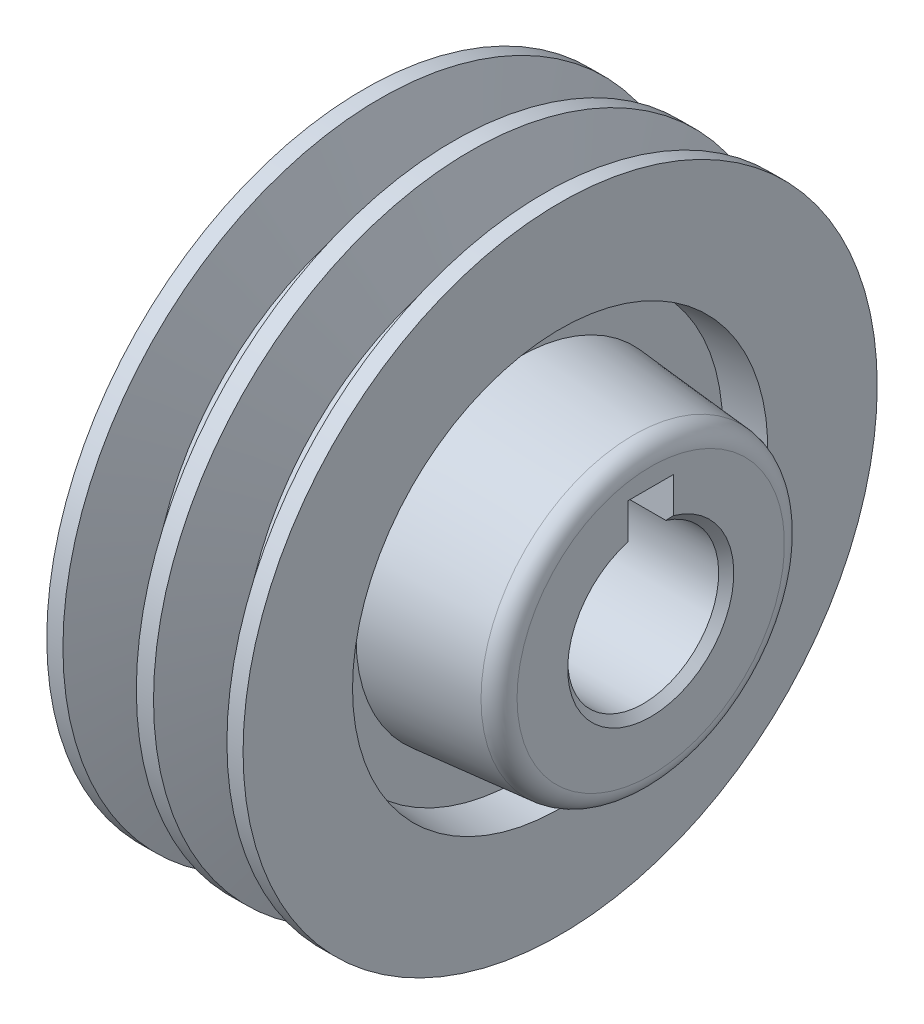
SolidWorks part; units mm, degrees
ref_plane "前视基准面" through (0, 0, 0) normal (0, 0, 1) x (1, 0, 0)
ref_plane "上视基准面" through (0, 0, 0) normal (0, 1, 0) x (1, 0, 0)
ref_plane "右视基准面" through (0, 0, 0) normal (1, 0, 0) x (0, 0, -1)
sketch "草图1" plane through (0, 0, 0) normal (0, 0, 1) x (1, 0, 0)
  line L0 (0, 0) -> (64.8368, 0) construction
  line L1 (-12, 10) -> (-12, 20)
  line L2 (0, 42) -> (26, 42)
  line L3 (26, 42) -> (26, 27.5)
  line L4 (-12, 20) -> (-41, 20) construction
  line L5 (5.5, 21.5311) -> (5.5, 27.0188)
  line L6 (38, 10) -> (-12, 10)
  line L7 (2.1385, 42) -> (4.8901, 33) construction
  line L8 (4.8901, 33) -> (9.1099, 33) construction
  line L9 (9.1099, 33) -> (11.8615, 42) construction
  line L10 (0, 40) -> (26, 40) construction
  line L11 (7, 33) -> (7, 10) construction
  line L12 (44, 27.5) -> (0, 27.5) construction
  line L13 (26, 27.5) -> (79, 27.5) construction
  line L14 (20.5, 27.0188) -> (20.5, 21.5311)
  line L15 (-6, 20) -> (38, 20) construction
  line L16 (13, 10) -> (13, 42) construction
  line L17 (38, 20) -> (38, 10)
  line L18 (0, 27.5) -> (0, 42)
  line L19 (5.5, 25.5) -> (20.5, 25.5) construction
  line L20 (5.5, 22) -> (20.5, 22) construction
  line L21 (26, 27.5) -> (26, 25.5) construction
  line L22 (26, 25.5) -> (20.5, 25.5) construction
  line L23 (20.5, 22) -> (38, 22) construction
  line L24 (38, 22) -> (38, 20) construction
  line L25 (20.5, 27.0188) -> (26, 27.5)
  line L26 (5.5, 27.0188) -> (0, 27.5)
  line L27 (5.5, 21.5311) -> (-12, 20)
  line L28 (20.5, 21.5311) -> (38, 20)
  point P17 (2.75, 40)
  point P18 (11.25, 40)
  dimension "d2" = 55
  dimension "L" = 50
  dimension "B" = 26
  dimension "d" = 20
  dimension "d1" = 40
  dimension "D3" = 5
  dimension "D4" = 5
  dimension "dd" = 80
  dimension "f" = 7
  dimension "槽轮角" = 34
  dimension "bd" = 8.5
  dimension "hf" = 7
  dimension "ha" = 2
  dimension "da" = 84
  dimension "S" = 15
  dimension "S2" = 2
revolve "旋转1" add sketch "草图1" angle 360 about L0
sketch "草图2" plane through (0, 0, 0) normal (0, 0, 1) x (1, 0, 0)
  line L0 (9.1099, 33) -> (11.8615, 42) construction
  line L1 (4.8901, 33) -> (9.1099, 33) construction
  line L2 (2.1385, 42) -> (4.8901, 33) construction
  line L3 (9.1099, 33) -> (11.8615, 42)
  line L4 (4.8901, 33) -> (9.1099, 33)
  line L5 (2.1385, 42) -> (4.8901, 33)
  line L6 (2.1385, 42) -> (11.8615, 42)
  line L7 (0, 0) -> (123, 0) construction
revolve "切除-旋转1" cut sketch "草图2" angle 360 about L7
pattern_linear "轮槽数" count 2 spacing 12 along (1, 0, 0) of "切除-旋转1"
chamfer "倒角1" distance 1 2 edges at (-12, 0, 10) (38, 0, 10)
sketch "草图4" plane through (-12, 0, 0) normal (-1, 0, 0) x (0, 0, 1)
  line L1 (-3, 9.5394) -> (3, 9.5394)
  line L2 (-3, 9.5394) -> (-3, 15.3)
  line L3 (-3, 15.3) -> (3, 15.3)
  line L4 (3, 9.5394) -> (3, 15.3)
  circle A0 centre (0, 0) radius 10 construction
  point P6 (-0.3, 15.3)
  dimension "键槽高度" = 15.3
  dimension "键槽宽度" = 6
  dimension "t1" = 3.3
extrude "切除-拉伸1" cut sketch "草图4" against normal through all
fillet "圆角2" radius 2.5 2 edges at (38, 0, 20) (-12, 0, 20)
sketch "草图5" plane through (0, 0, 0) normal (1, 0, 0) x (0, 0, -1)
  line L0 (0, 33) -> (0, 10) construction
  circle A0 centre (0, 23.75) radius 1.75
